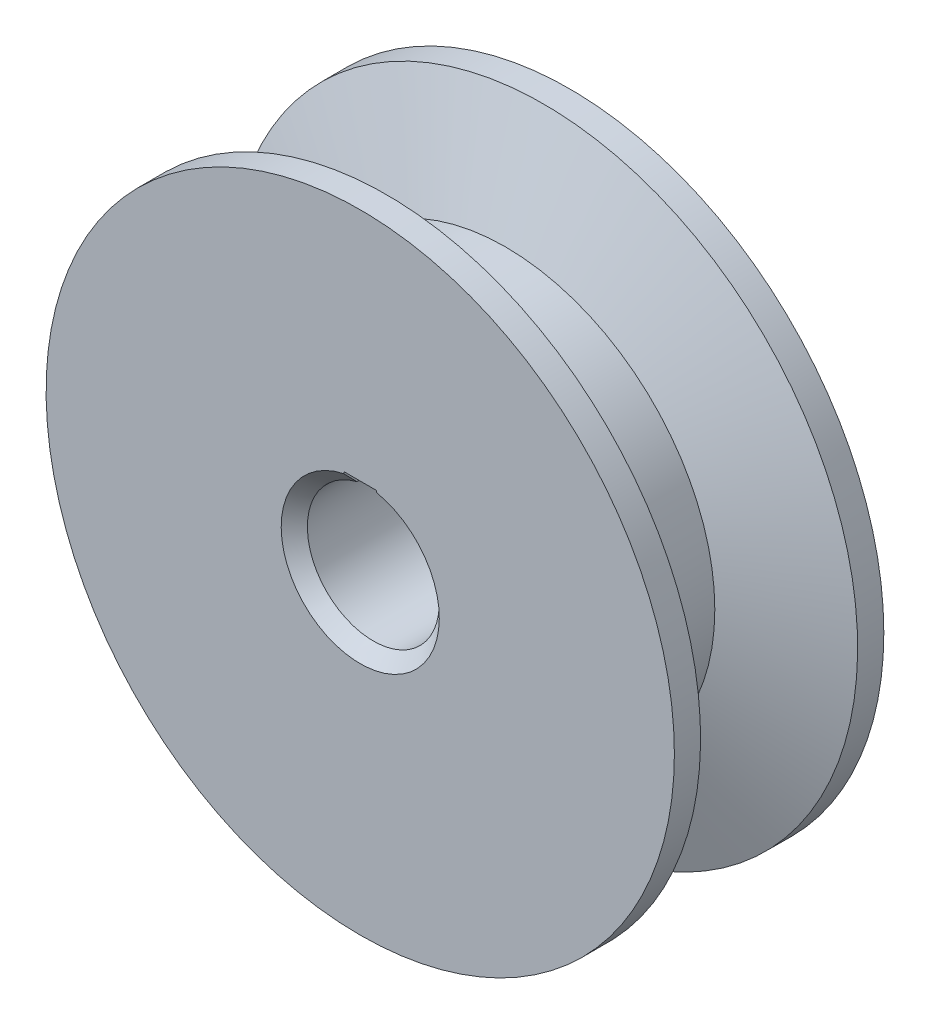
SolidWorks part; units mm, degrees
material "6061-T6 (SS)"
ref_plane "Front Plane" through (0, 0, 0) normal (0, 0, 1) x (1, 0, 0)
ref_plane "Top Plane" through (0, 0, 0) normal (0, 1, 0) x (1, 0, 0)
ref_plane "Right Plane" through (0, 0, 0) normal (1, 0, 0) x (0, 0, -1)
sketch "Sketch1" plane through (0, 0, 0) normal (0, 0, 1) x (1, 0, 0)
  circle A0 centre (0, 0) radius 19.05
  circle A1 centre (0, 0) radius 4
  dimension "D1" = 38.1
  dimension "D2" = 8
extrude "Extrude1" add sketch "Sketch1" along normal mid plane 12.7
sketch "Sketch2" plane through (0, 0, 0) normal (1, 0, 0) x (0, 0, -1)
  line L0 (-4.7625, 19.05) -> (4.7625, 19.05)
  line L2 (4.7625, 19.05) -> (2.4513, 12.7)
  line L3 (2.4513, 12.7) -> (-2.4513, 12.7)
  line L4 (-2.4513, 12.7) -> (-4.7625, 19.05)
  line L5 (-6.35, 0) -> (6.35, 0) construction
  line L6 (-6.35, 19.05) -> (-6.35, -19.05) construction
  line L7 (6.35, -19.05) -> (6.35, 19.05) construction
  point P2 (0, 19.05)
  point P5 (0, 12.7)
  dimension "D1" = 19.05
  dimension "D2" = 6.35
  dimension "D3" = 9.525
  dimension "D4" = 40
chamfer "Chamfer1" distance 0.7937 angle 45 2 edges at (4, 0, -6.35) (4, 0, 6.35)
revolve "Cut-Revolve1" cut sketch "Sketch2" angle 360 about L5
sketch "Sketch3" plane through (0, 0, 6.35) normal (0, 0, 1) x (1, 0, 0)
  line L0 (0, 0) -> (0, 3.8) construction
  line L2 (-1, 4.8) -> (1, 4.8)
  line L3 (-1, 4.8) -> (-1, 2.8)
  line L4 (-1, 2.8) -> (1, 2.8)
  line L5 (1, 4.8) -> (1, 2.8)
  line L6 (-1, 4.8) -> (1, 2.8) construction
  line L7 (-1, 2.8) -> (1, 4.8) construction
  dimension "D1" = 2.8
  dimension "D2" = 2
  dimension "D3" = 2
extrude "Cut-Extrude1" cut sketch "Sketch3" against normal through all contours L4 L5 L2 L3
